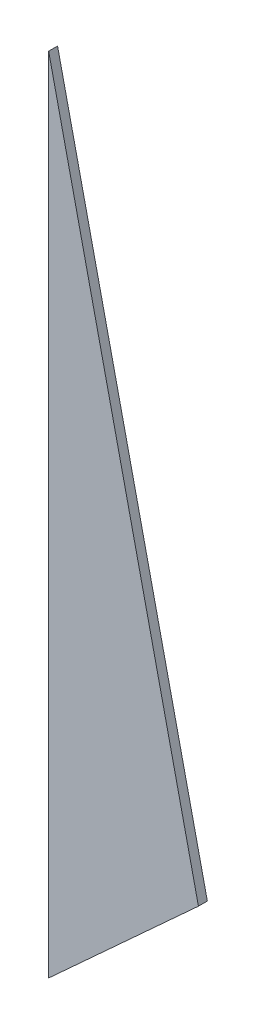
SolidWorks part; units mm, degrees
ref_plane "Front Plane" through (0, 0, 0) normal (0, 0, 1) x (1, 0, 0)
ref_plane "Top Plane" through (0, 0, 0) normal (0, 1, 0) x (1, 0, 0)
ref_plane "Right Plane" through (0, 0, 0) normal (1, 0, 0) x (0, 0, -1)
sketch "Sketch1" plane through (0, 0, 0) normal (0, 0, 1) x (1, 0, 0)
  line L0 (0, -45) -> (0, 45)
  line L1 (0, 45) -> (16.7943, -29.6323)
  line L2 (0, -45) -> (16.7943, -29.6323)
  line L4 (18, 252.4477) -> (18, -45) construction
  point P4 (0, 0)
extrude "Boss-Extrude1" add sketch "Sketch1" along normal mid plane 1
